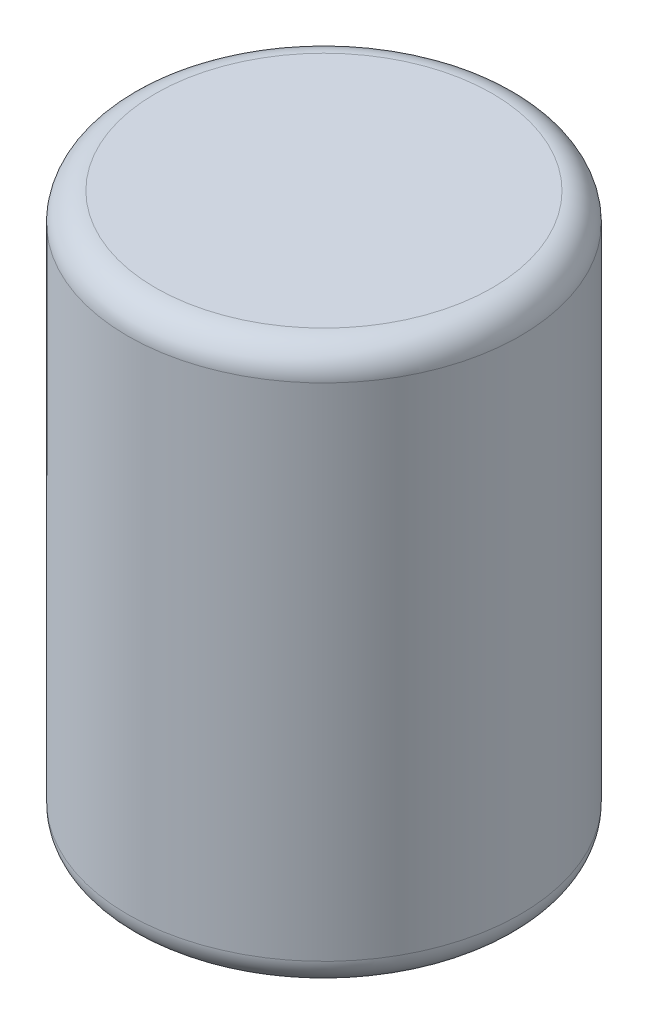
SolidWorks part; units mm, degrees
ref_plane "Front Plane" through (0, 0, 0) normal (0, 0, 1) x (1, 0, 0)
ref_plane "Top Plane" through (0, 0, 0) normal (0, 1, 0) x (1, 0, 0)
ref_plane "Right Plane" through (0, 0, 0) normal (1, 0, 0) x (0, 0, -1)
sketch "Sketch1" plane through (0, 0, 0) normal (0, 1, 0) x (1, 0, 0)
  circle A0 centre (0, 0) radius 14.1
  dimension "D1" = 28.2
extrude "Boss-Extrude1" add sketch "Sketch1" along normal blind 40
fillet "Fillet1" radius 2 2 edges at (0, 0, 14.1) (0, 40, 14.1)
